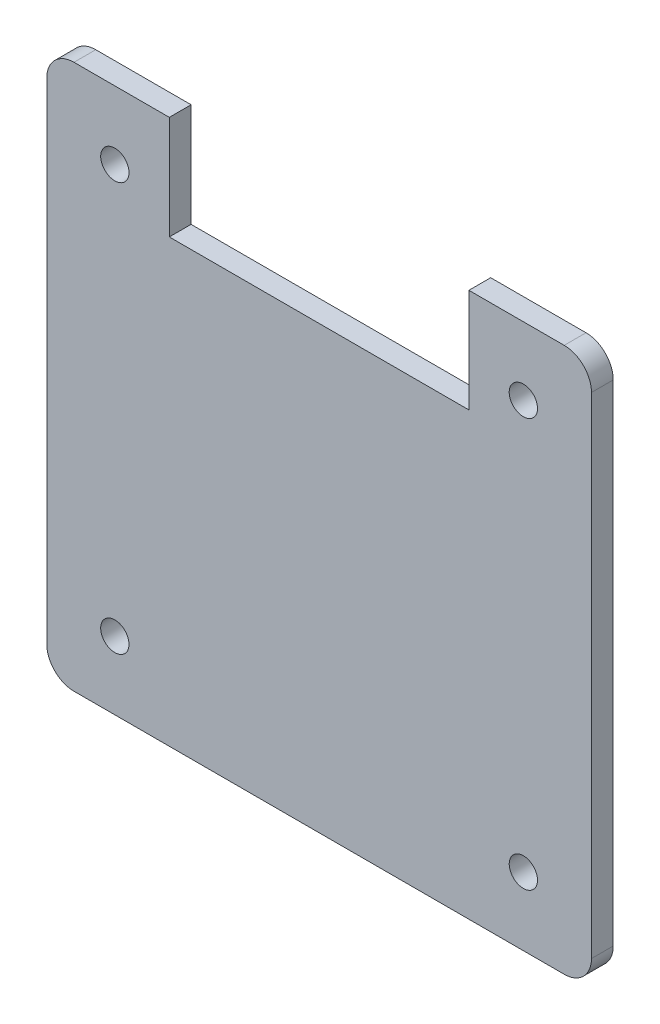
SolidWorks part; units mm, degrees
ref_plane "Front Plane" through (0, 0, 0) normal (0, 0, 1) x (1, 0, 0)
ref_plane "Top Plane" through (0, 0, 0) normal (0, 1, 0) x (1, 0, 0)
ref_plane "Right Plane" through (0, 0, 0) normal (1, 0, 0) x (0, 0, -1)
sketch "Sketch1" plane through (0, 0, 0) normal (0, 0, 1) x (1, 0, 0)
  line L1 (50, -50) -> (-50, -50)
  line L2 (50, -50) -> (50, 50)
  line L3 (50, 50) -> (-50, 50)
  line L4 (-50, -50) -> (-50, 50)
  line L5 (50, -50) -> (-50, 50) construction
  line L6 (50, 50) -> (-50, -50) construction
  point P0 (0, 0)
  dimension "D1" = 100
  dimension "D2" = 100
extrude "Boss-Extrude1" add sketch "Sketch1" along normal blind 4
sketch "Sketch2" plane through (0, 0, 4) normal (0, 0, 1) x (1, 0, 0)
  line L1 (37.5, -37.5) -> (-37.5, -37.5) construction
  line L2 (37.5, -37.5) -> (37.5, 37.5) construction
  line L3 (37.5, 37.5) -> (-37.5, 37.5) construction
  line L4 (-37.5, -37.5) -> (-37.5, 37.5) construction
  line L5 (37.5, -37.5) -> (-37.5, 37.5) construction
  line L6 (37.5, 37.5) -> (-37.5, -37.5) construction
  circle A0 centre (-37.5, 37.5) radius 2.6
  circle A1 centre (-37.5, -37.5) radius 2.6
  circle A2 centre (37.5, -37.5) radius 2.6
  circle A3 centre (37.5, 37.5) radius 2.6
  point P0 (0, 0)
  dimension "D3" = 5.2
  dimension "D1" = 75
  dimension "D2" = 75
extrude "Cut-Extrude1" cut sketch "Sketch2" against normal blind 4
fillet "Fillet1" radius 5 4 edges at (50, -50, 2) (-50, -50, 2) (-50, 50, 2) (50, 50, 2)
sketch "Sketch3" plane through (0, 0, 0) normal (0, 0, -1) x (-1, 0, 0)
  line L1 (27.5, 30.982) -> (-27.5, 30.982)
  line L2 (27.5, 30.982) -> (27.5, 55.982)
  line L3 (27.5, 55.982) -> (-27.5, 55.982)
  line L4 (-27.5, 30.982) -> (-27.5, 55.982)
  line L5 (27.5, 30.982) -> (-27.5, 55.982) construction
  line L6 (27.5, 55.982) -> (-27.5, 30.982) construction
  point P0 (0, 43.482)
  point P5 (0, 43.482)
  dimension "D1" = 55
  dimension "D2" = 0
  dimension "D3" = 25
extrude "Cut-Extrude2" cut sketch "Sketch3" against normal blind 4
